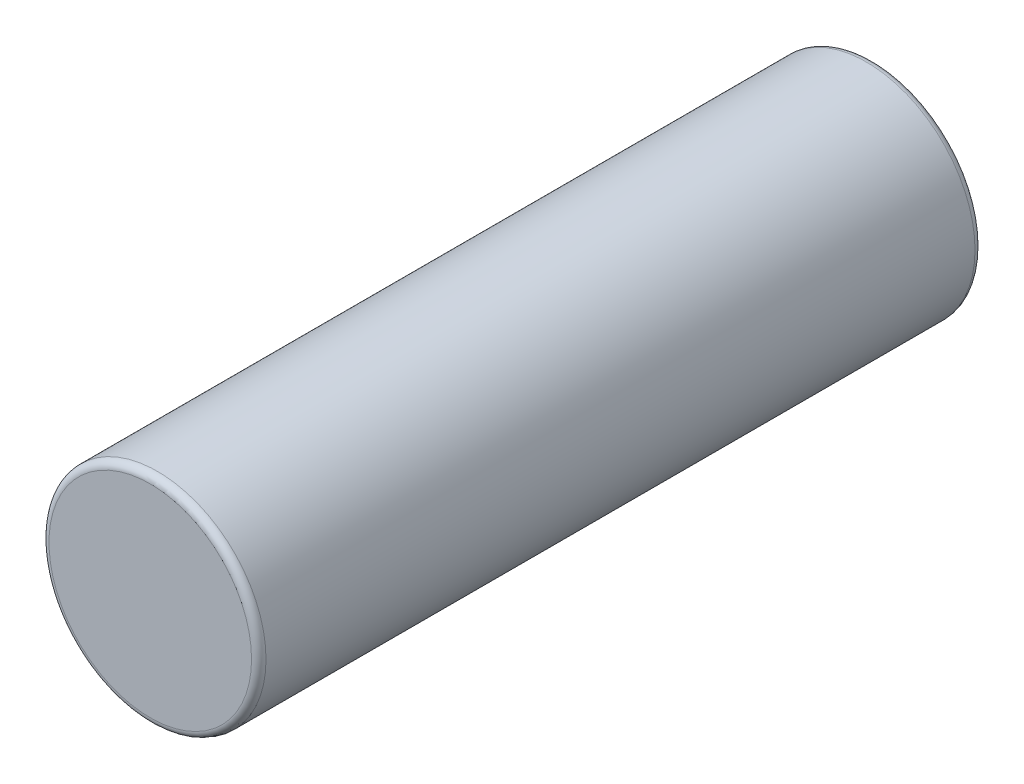
SolidWorks part; units mm, degrees
material "304不锈钢"
ref_plane "前视基准面" through (0, 0, 0) normal (0, 0, 1) x (1, 0, 0)
ref_plane "上视基准面" through (0, 0, 0) normal (0, 1, 0) x (1, 0, 0)
ref_plane "右视基准面" through (0, 0, 0) normal (1, 0, 0) x (0, 0, -1)
sketch "草图1" plane through (0, 0, 0) normal (0, 0, 1) x (1, 0, 0)
  circle A0 centre (0, 0) radius 1.5
  dimension "D1" = 3
extrude "凸台-拉伸1" add sketch "草图1" along normal blind 10
fillet "圆角1" radius 0.1 2 edges at (1.5, 0, 0) (1.5, 0, 10)
